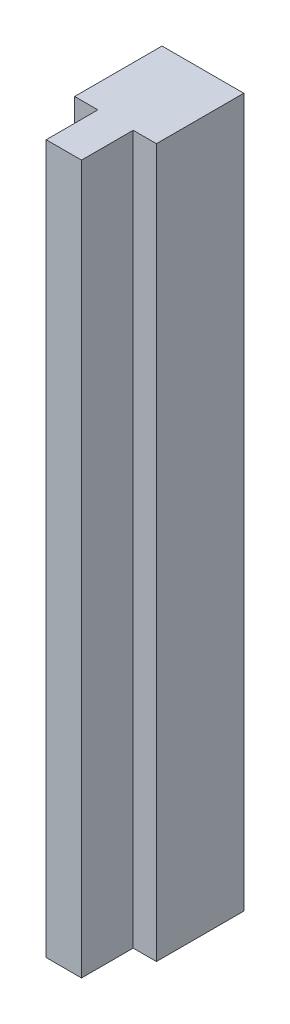
SolidWorks part; units mm, degrees
ref_plane "前基準面" through (0, 0, 0) normal (0, 0, 1) x (1, 0, 0)
ref_plane "上基準面" through (0, 0, 0) normal (0, 1, 0) x (1, 0, 0)
ref_plane "右基準面" through (0, 0, 0) normal (1, 0, 0) x (0, 0, -1)
sketch "草圖1" plane through (0, 0, 0) normal (0, 1, 0) x (1, 0, 0)
  line L1 (-2.5, 2.5) -> (2.5, 2.5)
  line L2 (-2.5, 2.5) -> (-2.5, -2.5)
  line L3 (-2.5, -2.5) -> (2.5, -2.5)
  line L4 (2.5, 2.5) -> (2.5, -2.5)
  line L5 (-2.5, 2.5) -> (2.5, -2.5) construction
  line L6 (-2.5, -2.5) -> (2.5, 2.5) construction
  point P0 (0, 0)
  dimension "D1" = 5
  dimension "D2" = 5
extrude "填料-伸長1" add sketch "草圖1" along normal blind 38.1
sketch "草圖3" plane through (0, 38.1, 0) normal (0, 1, 0) x (1, 0, 0)
  line L0 (0, -1002.5) -> (0, 48997.5) construction
  line L1 (-2.5, -2.5) -> (2.5, -2.5) construction
  line L3 (-1, -2.5) -> (1, -2.5)
  line L4 (-1, -2.5) -> (-1, -5.28)
  line L5 (-1, -5.28) -> (1, -5.28)
  line L6 (1, -2.5) -> (1, -5.28)
  line L7 (-1, -2.5) -> (1, -5.28) construction
  line L8 (-1, -5.28) -> (1, -2.5) construction
  point P1 (0, -3.89)
  point P5 (0, -2.5)
  dimension "D1" = 2
  dimension "D2" = 0
  dimension "D3" = 2.78
extrude "填料-伸長2" add sketch "草圖3" against normal blind 38.1
sketch "草圖6" plane through (0, 0, 0) normal (0, -1, 0) x (1, 0, 0)
  line L0 (-2.5, 2.5) -> (-1, 2.5) construction
  line L1 (-2.2, 2.2) -> (2.2, 2.2)
  line L2 (-2.2, 2.2) -> (-2.2, -2.2)
  line L3 (-2.2, -2.2) -> (2.2, -2.2)
  line L4 (2.2, 2.2) -> (2.2, -2.2)
  line L5 (-2.2, 2.2) -> (2.2, -2.2) construction
  line L6 (-2.2, -2.2) -> (2.2, 2.2) construction
  line L7 (-2.5, -2.5) -> (-2.5, 2.5) construction
  point P0 (0, 0)
  dimension "D1" = 0.3
  dimension "D2" = 0.3
extrude "除料-伸長-薄件1" cut sketch "草圖6" against normal through all thin thin type one direction wall 0.3
sketch "草圖8" plane through (0, 0, 0) normal (0, -1, 0) x (1, 0, 0)
  line L0 (1, 2.5) -> (2.2, 2.5)
  line L1 (2.2, 2.5) -> (2.2, 2.2)
  line L2 (2.2, 2.2) -> (-2.2, 2.2)
  line L3 (-2.2, 2.2) -> (-2.2, 2.5)
  line L4 (-2.2, 2.5) -> (1, 2.5)
extrude "填料-伸長3" add sketch "草圖8" against normal blind 38.1
sketch "草圖9" plane through (0, 0, 0) normal (0, -1, 0) x (1, 0, 0)
  line L0 (-1, 2.5) -> (-0.95, 2.5)
  line L1 (-0.95, 2.5) -> (-0.95, 5.28)
  line L2 (-1, 5.28) -> (1, 5.28) construction
  line L3 (-0.95, 5.28) -> (-1, 5.28)
  line L4 (-1, 5.28) -> (-1, 2.5)
  dimension "D1" = 0.05
extrude "除料-伸長1" cut sketch "草圖9" against normal through all
sketch "草圖11" plane through (0, 0, 0) normal (0, -1, 0) x (1, 0, 0)
  line L0 (1, 2.5) -> (0.95, 2.5)
  line L1 (0.95, 2.5) -> (0.95, 5.28)
  line L2 (-0.95, 5.28) -> (1, 5.28) construction
  line L3 (0.95, 5.28) -> (1, 5.28)
  line L4 (1, 5.28) -> (1, 2.5)
  dimension "D1" = 0.05
extrude "除料-伸長2" cut sketch "草圖11" against normal through all
